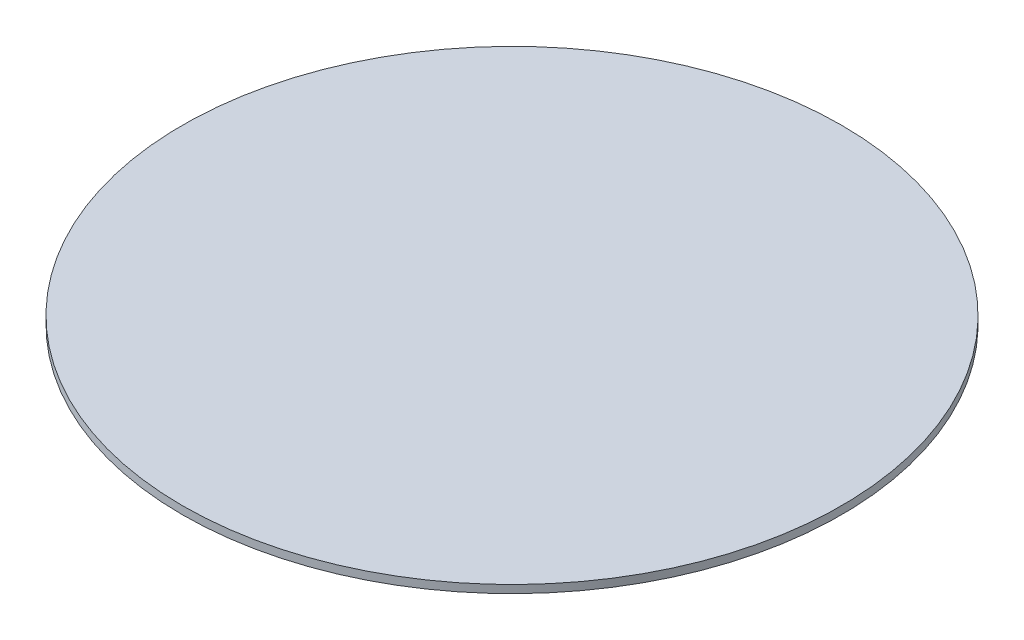
SolidWorks part; units mm, degrees
material "玻璃"
ref_plane "前视基准面" through (0, 0, 0) normal (0, 0, 1) x (1, 0, 0)
ref_plane "上视基准面" through (0, 0, 0) normal (0, 1, 0) x (1, 0, 0)
ref_plane "右视基准面" through (0, 0, 0) normal (1, 0, 0) x (0, 0, -1)
sketch "草图1" plane through (0, 0, 0) normal (0, 1, 0) x (1, 0, 0)
  circle A0 centre (0, 0) radius 125
  dimension "D1" = 250
extrude "凸台-拉伸1" add sketch "草图1" along normal blind 3
sketch "Sketch1" plane through (0, 3, 0) normal (0, 1, 0) x (1, 0, 0)
  point P0 (0, 0)
